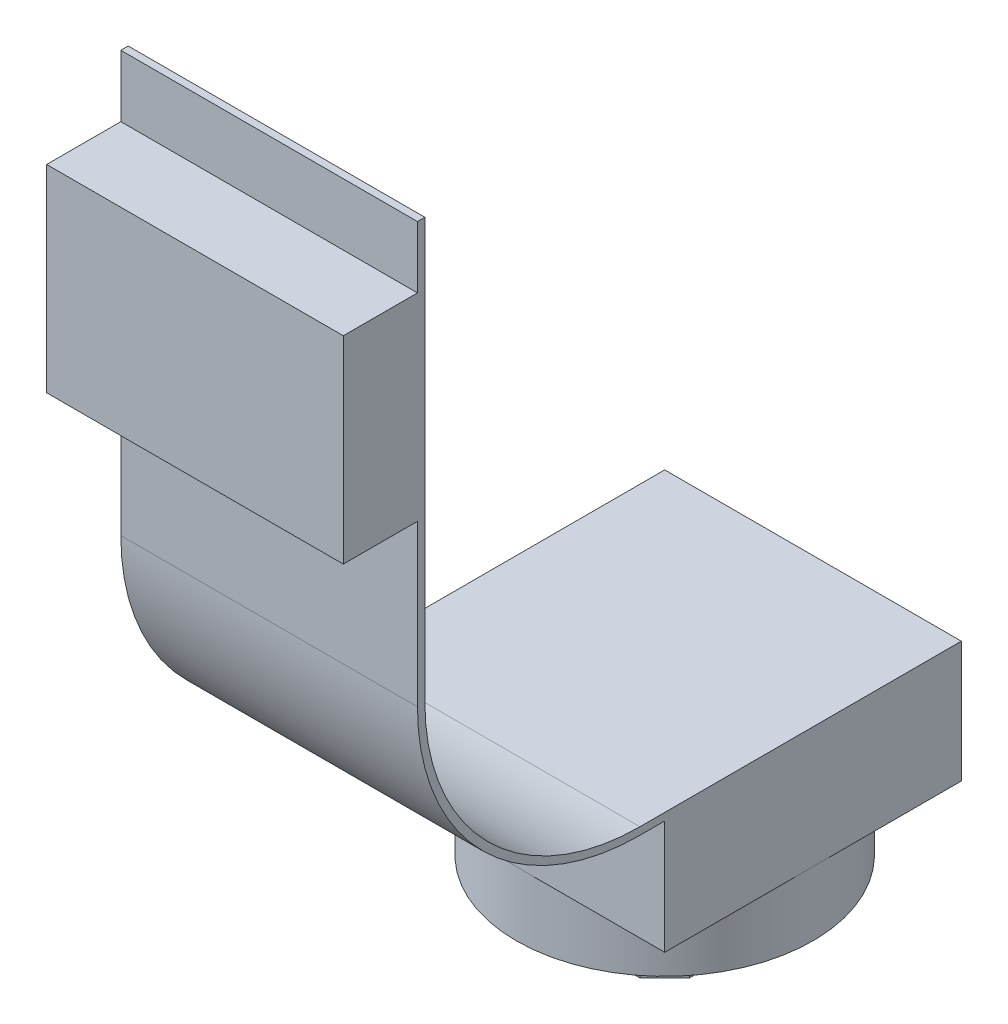
SolidWorks part; units mm, degrees
ref_plane "Piano frontale" through (0, 0, 0) normal (0, 0, 1) x (1, 0, 0)
ref_plane "Piano superiore" through (0, 0, 0) normal (0, 1, 0) x (1, 0, 0)
ref_plane "Piano destro" through (0, 0, 0) normal (1, 0, 0) x (0, 0, -1)
ref_plane "Piano4" through (-3, 0, 0) normal (-1, 0, 0) x (0, -1, 0)
sketch "Schizzo1" plane through (-3, 0, 0) normal (-1, 0, 0) x (0, -1, 0)
  line L0 (-13, 1.5) -> (-13, -11)
  line L1 (-13, -11) -> (2.3, -11)
  line L2 (2.3, -11) -> (2.3, 1.5)
  line L3 (2.3, 1.5) -> (-13, 1.5)
extrude "Estrusione-Estrusione1" add sketch "Schizzo1" against normal blind 6
sketch "Schizzo2" plane through (3, 0, 0) normal (1, 0, 0) x (0, 0, -1)
  line L0 (0, 11.75) -> (0, 13)
  line L1 (0, 13) -> (-1.5, 13)
  line L2 (-1.5, 13) -> (-1.5, 11.75)
  line L3 (-1.5, 11.75) -> (0, 11.75)
extrude "Taglio-Estrusione1" cut sketch "Schizzo2" against normal through all
sketch "Schizzo3" plane through (3, 0, 0) normal (1, 0, 0) x (0, 0, -1)
  line L0 (0.15, 0.15) -> (11, 0.15)
  line L1 (11, 0.15) -> (11, 13)
  line L2 (11, 13) -> (0.15, 13)
  line L3 (0.15, 13) -> (0.15, 0.15)
extrude "Taglio-Estrusione2" cut sketch "Schizzo3" against normal through all
sketch "Schizzo4" plane through (3, 0, 0) normal (1, 0, 0) x (0, 0, -1)
  line L0 (5, 0) -> (-1.5, 0)
  line L1 (-1.5, 0) -> (-1.5, -2.3)
  line L2 (-1.5, -2.3) -> (5, -2.3)
  line L3 (5, -2.3) -> (5, 0)
extrude "Taglio-Estrusione3" cut sketch "Schizzo4" against normal through all
sketch "Schizzo5" plane through (3, 0, 0) normal (1, 0, 0) x (0, 0, -1)
  line L0 (0, 7.75) -> (-1.5, 7.75)
  line L1 (-1.5, 7.75) -> (-1.5, 0)
  line L2 (-1.5, 0) -> (0, 0)
  line L3 (0, 0) -> (0, 7.75)
extrude "Taglio-Estrusione4" cut sketch "Schizzo5" against normal through all
ref_plane "Piano5" through (0, -3.6, 0) normal (0, -1, 0) x (1, 0, 0)
sketch "Schizzo6" plane through (0, -3.6, 0) normal (0, -1, 0) x (1, 0, 0)
  circle A0 centre (0, -8) radius 3
extrude "Estrusione-Estrusione2" add sketch "Schizzo6" against normal up to next
sketch "Schizzo7" plane through (0, -3.6, 0) normal (0, -1, 0) x (1, 0, 0)
  line L0 (-2, -10) -> (-2, -6)
  line L1 (-2, -6) -> (2, -6)
  line L2 (2, -6) -> (2, -10)
  line L3 (2, -10) -> (-2, -10)
extrude "Estrusione-Estrusione3" add sketch "Schizzo7" along normal blind 0.4
sketch "Schizzo8" plane through (0, -4, 0) normal (0, -1, 0) x (1, 0, 0)
  circle A0 centre (0, -8) radius 0.2451
extrude "Estrusione-Estrusione4" [suppressed] add sketch "Schizzo8" along normal blind 59.6 draft 31.5
chamfer "Smusso1" distance 0.5 angle 45 1 edges at (-2, -3.8, -10)
chamfer "Smusso2" distance 0.5 angle 45 1 edges at (2, -3.8, -6)
chamfer "Smusso3" distance 0.5 angle 45 1 edges at (-2, -3.8, -6)
chamfer "Smusso4" distance 0.5 angle 45 1 edges at (2, -3.8, -10)
fillet "Raccordo1" radius 4.35 1 edges at (0, 0.15, -0.15)
fillet "Raccordo2" radius 4.5 1 edges at (0, 0, 0)
